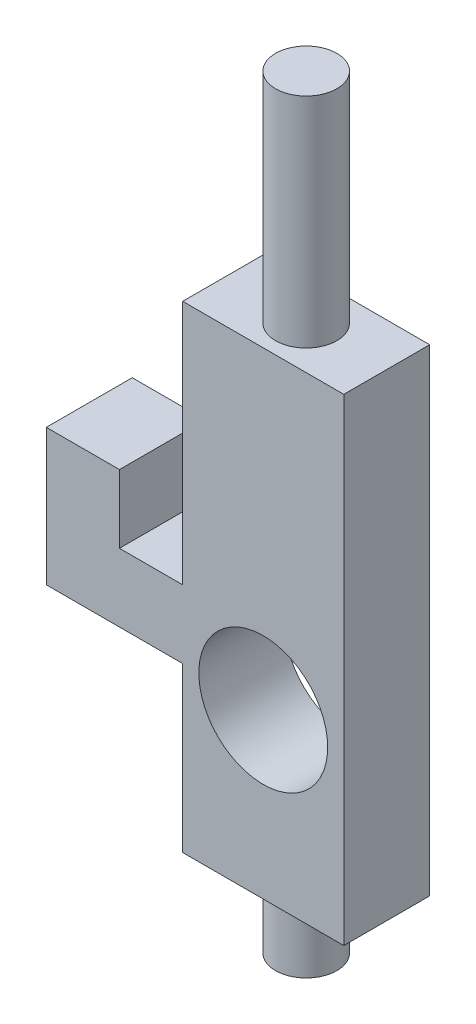
SolidWorks part; units mm, degrees
ref_plane "Front Plane" through (0, 0, 0) normal (0, 0, 1) x (1, 0, 0)
ref_plane "Top Plane" through (0, 0, 0) normal (0, 1, 0) x (1, 0, 0)
ref_plane "Right Plane" through (0, 0, 0) normal (1, 0, 0) x (0, 0, -1)
sketch "Sketch1" plane through (0, 0, 0) normal (0, 1, 0) x (1, 0, 0)
  circle A1 centre (0, 0) radius 2.855
  dimension "D1" = 5.71
extrude "Boss-Extrude1" add sketch "Sketch1" along normal blind 6.35
sketch "Sketch2" plane through (0, 6.35, 0) normal (0, 1, 0) x (1, 0, 0)
  line L1 (-7.5, 4) -> (7.5, 4)
  line L2 (-7.5, 4) -> (-7.5, -4)
  line L3 (-7.5, -4) -> (7.5, -4)
  line L4 (7.5, 4) -> (7.5, -4)
  line L5 (-7.5, 4) -> (7.5, -4) construction
  line L6 (-7.5, -4) -> (7.5, 4) construction
  point P0 (0, 0)
  dimension "D1" = 8
  dimension "D2" = 15
extrude "Boss-Extrude2" add sketch "Sketch2" along normal blind 44.45
sketch "Sketch3" plane through (0, 0, 4) normal (0, 0, 1) x (1, 0, 0)
  line L0 (0, 50.8) -> (0, -2.7923) construction
  line L1 (-7.5, 50.8) -> (7.5, 50.8) construction
  circle A0 centre (0, 21.59) radius 6
  dimension "D2" = 12
extrude "Cut-Extrude1" cut sketch "Sketch3" against normal blind 25.4
sketch "Sketch4" plane through (0, 50.8, 0) normal (0, 1, 0) x (1, 0, 0)
  circle A0 centre (0, 0) radius 2.855
  point P0 (0, 0)
  dimension "D1" = 5.71
extrude "Boss-Extrude3" add sketch "Sketch4" along normal blind 20.32
sketch "Sketch5" plane through (-7.5, 0, 0) normal (-1, 0, 0) x (0, 0, 1)
  line L0 (4, 50.8) -> (4, 6.35) construction
  line L1 (-4, 21.59) -> (4, 21.59)
  line L2 (-4, 21.59) -> (-4, 27.94)
  line L3 (-4, 27.94) -> (4, 27.94)
  line L4 (4, 21.59) -> (4, 27.94)
  line L5 (-4, 21.59) -> (4, 27.94) construction
  line L6 (-4, 27.94) -> (4, 21.59) construction
  point P0 (0, 24.765)
  dimension "D1" = 6.35
extrude "Boss-Extrude4" add sketch "Sketch5" along normal blind 12.7
sketch "Sketch6" plane through (0, 27.94, 0) normal (0, 1, 0) x (1, 0, 0)
  line L1 (-13.3877, -4) -> (-20.2, -4)
  line L2 (-13.3877, -4) -> (-13.3877, 4)
  line L3 (-13.3877, 4) -> (-20.2, 4)
  line L4 (-20.2, -4) -> (-20.2, 4)
  line L5 (-13.3877, -4) -> (-20.2, 4) construction
  line L6 (-13.3877, 4) -> (-20.2, -4) construction
  point P0 (-16.7938, 0)
extrude "Boss-Extrude5" add sketch "Sketch6" along normal blind 6.35
